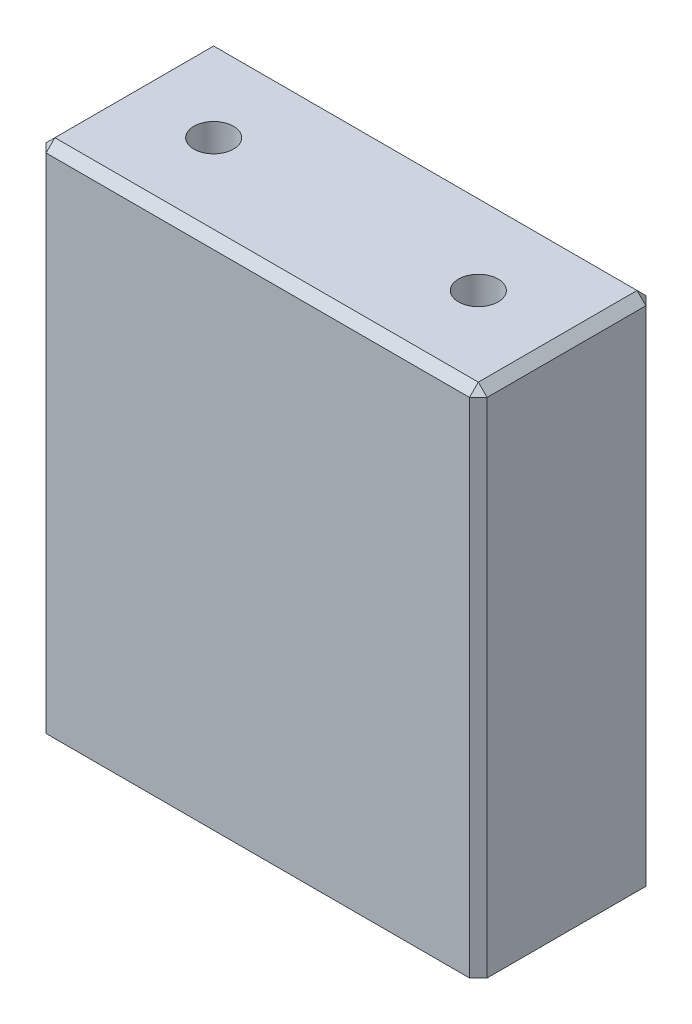
SolidWorks part; units mm, degrees
ref_plane "Front Plane" through (0, 0, 0) normal (0, 0, 1) x (1, 0, 0)
ref_plane "Top Plane" through (0, 0, 0) normal (0, 1, 0) x (1, 0, 0)
ref_plane "Right Plane" through (0, 0, 0) normal (1, 0, 0) x (0, 0, -1)
sketch "Sketch1" plane through (0, 0, 0) normal (0, 0, 1) x (1, 0, 0)
  line L0 (0, 0) -> (0, 80) construction
  line L1 (0, 80) -> (0, 85) construction
  line L2 (0, 85) -> (0, 90) construction
  line L3 (0, 90) -> (0, 95) construction
  line L4 (0, 95) -> (10, 95) construction
  line L5 (10, 95) -> (10, 90) construction
  line L6 (10, 90) -> (10, 78) construction
  line L7 (10, 78) -> (10, 58) construction
  line L8 (10, 58) -> (10, 0)
  line L9 (10, 0) -> (60, 0)
  line L10 (60, 0) -> (60, 58)
  line L11 (60, 58) -> (10, 58)
  dimension "D1" = 80
  dimension "D2" = 5
  dimension "D3" = 5
  dimension "D4" = 5
  dimension "D5" = 5
  dimension "D6" = 12
  dimension "D7" = 20
  dimension "D8" = 10
  dimension "D9" = 50
extrude "Boss-Extrude1" add sketch "Sketch1" along normal blind 20
sketch "Sketch2" plane through (0, 58, 0) normal (0, 1, 0) x (1, 0, 0)
  line L0 (35, 0) -> (35, -20) construction
  line L1 (60, 0) -> (10, 0) construction
  line L2 (60, -20) -> (10, -20) construction
  line L3 (20, -10) -> (50, -10) construction
  line L4 (10, -20) -> (10, 0) construction
  circle A0 centre (20, -10) radius 2.25
  circle A1 centre (50, -10) radius 2.25
  point P9 (35, -10)
  dimension "D1" = 4.5
  dimension "D2" = 10
extrude "Cut-Extrude1" cut sketch "Sketch2" against normal through all
sketch "Sketch3" plane through (0, 0, 0) normal (0, -1, 0) x (1, 0, 0)
  line L0 (10, 20) -> (60, 0) construction
  line L1 (10, 20) -> (60, 20) construction
  line L2 (13, 3) -> (57, 3)
  line L3 (13, 3) -> (13, 17)
  line L4 (13, 17) -> (57, 17)
  line L5 (57, 3) -> (57, 17)
  line L6 (13, 3) -> (57, 17) construction
  line L7 (13, 17) -> (57, 3) construction
  line L8 (10, 20) -> (10, 0) construction
  point P4 (35, 10)
  dimension "D1" = 3
  dimension "D2" = 3
extrude "Cut-Extrude2" cut sketch "Sketch3" against normal offset from surface (53 mm away) 5 up to face at (17.75, 58, 10)
chamfer "Chamfer1" distance 1 angle 45 8 edges at (60, 29, 20) (60, 29, 0) (10, 29, 0) (10, 29, 20) (10, 58, 10) (35, 58, 0) (60, 58, 10) (35, 58, 20)
